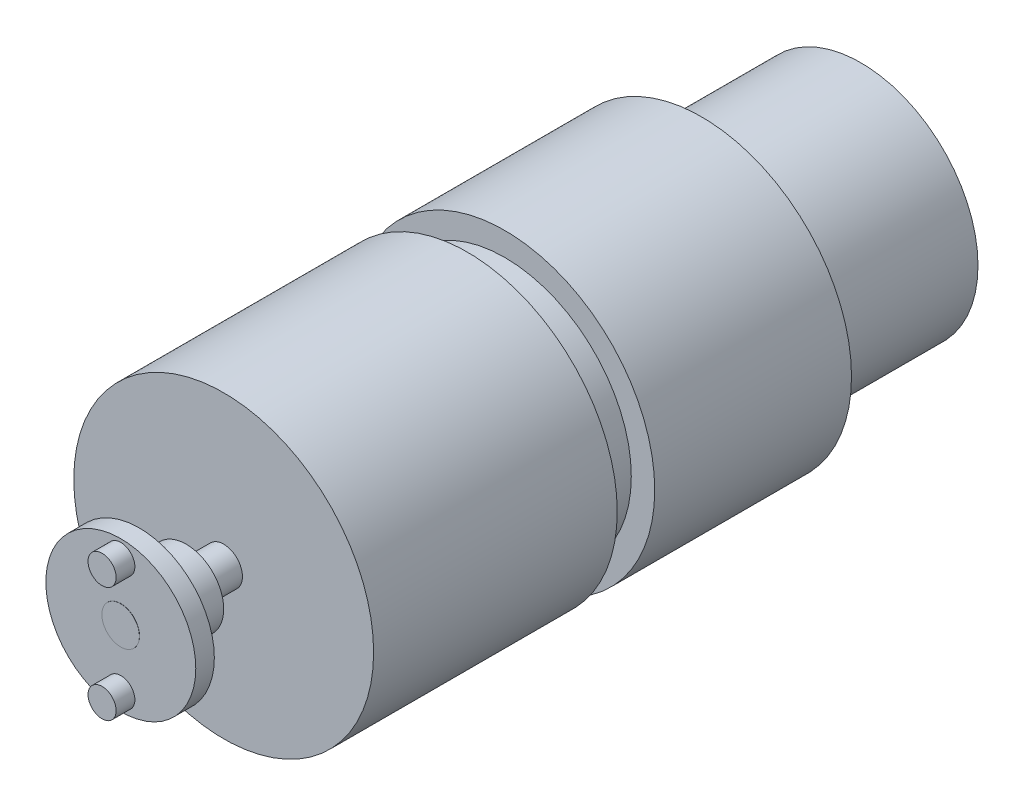
SolidWorks part; units mm, degrees
ref_plane "Спереди" through (0, 0, 0) normal (0, 0, 1) x (1, 0, 0)
ref_plane "Сверху" through (0, 0, 0) normal (0, 1, 0) x (1, 0, 0)
ref_plane "Справа" through (0, 0, 0) normal (1, 0, 0) x (0, 0, -1)
sketch "Эскиз1" plane through (0, 0, 0) normal (0, 0, 1) x (1, 0, 0)
  circle A0 centre (0, 0) radius 12.5
  dimension "D1" = 25
extrude "Вытянуть1" add sketch "Эскиз1" along normal blind 17
sketch "Эскиз2" plane through (0, 0, 17) normal (0, 0, 1) x (1, 0, 0)
  circle A0 centre (0, 0) radius 16
  dimension "D1" = 32
extrude "Вытянуть2" add sketch "Эскиз2" along normal blind 51
sketch "Эскиз3" plane through (0, 0, 68) normal (0, 0, 1) x (1, 0, 0)
  circle A0 centre (0, 0) radius 2
  dimension "D1" = 4
extrude "Вытянуть3" add sketch "Эскиз3" along normal blind 11
ref_plane "Плоскость1" through (0, 0, 72) normal (0, 0, 1) x (1, 0, 0)
sketch "Эскиз4" plane through (0, 0, 72) normal (0, 0, 1) x (1, 0, 0)
  circle A0 centre (0, 0) radius 4
extrude "Вытянуть4" add sketch "Эскиз4" along normal blind 5
sketch "Эскиз5" plane through (0, 0, 77) normal (0, 0, 1) x (1, 0, 0)
  circle A0 centre (0, 0) radius 8
  dimension "D1" = 16
extrude "Вытянуть5" add sketch "Эскиз5" along normal blind 1.98
sketch "Эскиз6" plane through (0, 0, 78.98) normal (0, 0, 1) x (1, 0, 0)
  circle A0 centre (0, -6.1549) radius 1.5
  circle A1 centre (0, 6.1549) radius 1.5
  dimension "D1" = 3
  dimension "D2" = 3
extrude "Вытянуть6" add sketch "Эскиз6" along normal blind 2
ref_plane "Плоскость2" through (0, 0, 38) normal (0, 0, 1) x (1, 0, 0)
sketch "Эскиз7" plane through (0, 0, 38) normal (0, 0, 1) x (1, 0, 0)
  circle A0 centre (0, 0) radius 13.5
  circle A1 centre (0, 0) radius 20.7825
  dimension "D1" = 27
  dimension "D2" = 41.565
extrude "Вытянуть8" cut sketch "Эскиз7" along normal blind 4
